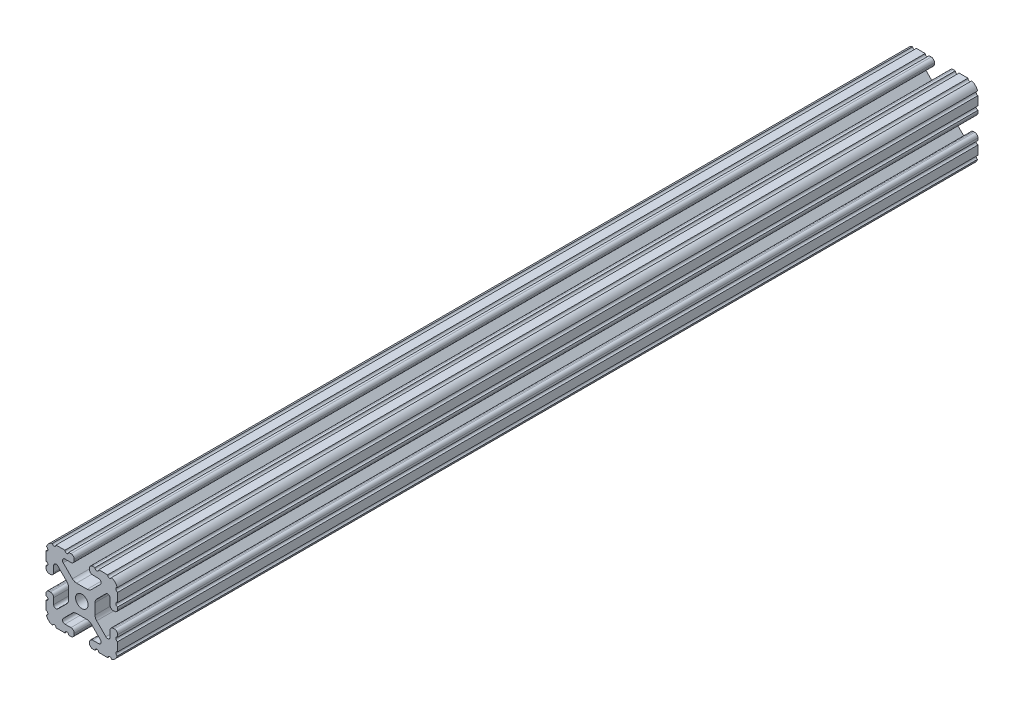
SolidWorks part; units mm, degrees
ref_plane "Front Plane" through (0, 0, 0) normal (0, 0, 1) x (1, 0, 0)
ref_plane "Top Plane" through (0, 0, 0) normal (0, 1, 0) x (1, 0, 0)
ref_plane "Right Plane" through (0, 0, 0) normal (1, 0, 0) x (0, 0, -1)
sketch "Sketch2" plane through (0, 0, 0) normal (0, 0, 1) x (1, 0, 0)
  line L0 (0, 19.05) -> (0, -19.05) construction
  line L1 (-19.05, 0) -> (19.05, 0) construction
  line L2 (4.064, -19.05) -> (19.05, -19.05)
  line L3 (19.05, -19.05) -> (19.05, -4.064)
  line L4 (4.064, -19.05) -> (4.064, -14.986)
  line L5 (4.064, -14.986) -> (12.1123, -14.986)
  line L6 (12.1123, -14.986) -> (4.1113, -6.985)
  line L7 (0, 0) -> (19.05, -19.05) construction
  line L8 (19.05, -4.064) -> (14.986, -4.064)
  line L9 (14.986, -4.064) -> (14.986, -12.1123)
  line L10 (14.986, -12.1123) -> (6.985, -4.1113)
  circle A0 centre (0, 0) radius 3.3274
  arc A1 (8.9963, -14.986) -> (9.909, -12.7826) centre (8.9963, -13.6953) ccw construction
  point P8 (0, -6.985)
  dimension "Center Hole Diameter" = 6.6548
  dimension "Rail Height" = 38.1
  dimension "Rail Width" = 38.1
  dimension "T-Slot Width" = 8.128
  dimension "Slot Inner Width" = 20.574
  dimension "Thickness" = 4.064
  dimension "Slot Depth" = 8.001
  dimension "D1" = 4.064
sketch "Sketch3" plane through (0, 0, 0) normal (1, 0, 0) x (0, 0, -1)
  line L0 (-228.6, -19.05) -> (228.6, -19.05) construction
  line L1 (-203.2, 0) -> (203.2, 0) construction
  dimension "Length" = 457.2
  dimension "D1" = 25.4
sketch "Sketch4" plane through (0, 0, 0) normal (0, 0, 1) x (1, 0, 0)
  line L0 (5.7912, -19.05) -> (14.3002, -19.05)
  line L1 (4.064, -19.05) -> (19.05, -19.05) construction
  line L2 (4.064, -19.05) -> (4.064, -14.986) construction
  line L3 (4.064, -14.986) -> (12.1123, -14.986) construction
  line L4 (4.064, -16.7132) -> (4.064, -17.3228)
  line L5 (5.7912, -14.986) -> (8.9963, -14.986)
  line L6 (0, -6.985) -> (2.833, -6.985)
  line L7 (12.1123, -14.986) -> (4.1113, -6.985) construction
  line L8 (5.0152, -7.8889) -> (9.909, -12.7826)
  line L9 (19.05, -19.05) -> (19.05, -4.064) construction
  line L10 (14.986, -12.1123) -> (6.985, -4.1113) construction
  line L11 (14.986, -4.064) -> (14.986, -12.1123) construction
  line L12 (14.986, -8.9963) -> (14.986, -5.7912)
  line L13 (19.05, -4.064) -> (14.986, -4.064) construction
  line L14 (16.7132, -4.064) -> (17.3228, -4.064)
  line L15 (19.05, -5.7912) -> (19.05, -14.3002)
  line L16 (12.7826, -9.909) -> (7.8889, -5.0152)
  line L17 (6.985, 0) -> (6.985, -2.833)
  line L18 (-19.05, 0) -> (19.05, 0) construction
  line L19 (0, -6.985) -> (0, -3.3274)
  line L20 (0, 19.05) -> (0, -19.05) construction
  line L21 (6.985, 0) -> (3.3274, 0)
  arc A0 (4.064, -17.3228) -> (5.7912, -19.05) centre (5.7912, -17.3228) ccw
  arc A2 (4.064, -16.7132) -> (5.7912, -14.986) centre (5.7912, -16.7132) cw
  arc A3 (8.9963, -14.986) -> (9.909, -12.7826) centre (8.9963, -13.6953) ccw
  arc A4 (2.833, -6.985) -> (5.0152, -7.8889) centre (2.833, -10.0711) cw
  arc A5 (14.3002, -19.05) -> (19.05, -14.3002) centre (14.3002, -14.3002) ccw
  arc A6 (12.7826, -9.909) -> (14.986, -8.9963) centre (13.6953, -8.9963) ccw
  arc A7 (14.986, -5.7912) -> (16.7132, -4.064) centre (16.7132, -5.7912) cw
  arc A8 (17.3228, -4.064) -> (19.05, -5.7912) centre (17.3228, -5.7912) cw
  arc A9 (7.8889, -5.0152) -> (6.985, -2.833) centre (10.0711, -2.833) cw
  circle A10 centre (0, 0) radius 3.3274 construction
  arc A11 (0, -3.3274) -> (3.3274, 0) centre (0, 0) ccw
  dimension "D1" = 4.7498
  dimension "D2" = 3.0861
  dimension "D3" = 1.7272
extrude "Boss-Extrude1" add sketch "Sketch4" along normal mid plane 457.2
sketch "Sketch5" plane through (0, 0, 0) normal (0, 0, 1) x (1, 0, 0)
  line L0 (4.064, -19.05) -> (19.05, -19.05) construction
  line L1 (5.7912, -14.986) -> (8.9963, -14.986) construction
  line L3 (0, 0) -> (19.05, -19.05) construction
  line L4 (8.9963, -14.986) -> (8.9963, -19.05) construction
  line L5 (12.1123, -14.986) -> (4.1113, -6.985) construction
  circle A0 centre (14.7395, -19.05) radius 1.016
  circle A1 centre (7.9803, -19.05) radius 1.016
  circle A2 centre (19.05, -14.7395) radius 1.016
  circle A3 centre (19.05, -7.9803) radius 1.016
  point P10 (7.3938, -14.986)
  point P12 (13.6953, -8.9963)
  dimension "D1" = 2.032
extrude "Cut-Extrude1" cut sketch "Sketch5" against normal through all both and the other way through all
mirror "Mirror1" about plane through (0, 0, 0) normal (1, 0, 0) of bodies 137 134
mirror "Mirror2" about plane through (0, 0, 0) normal (0, 1, 0) of bodies 135
equation "\"D1@Boss-Extrude1\"=\"Length@Sketch3\""
equation "\"D1@Sketch2\"=\"Thickness@Sketch2\""
equation "\"D2@Sketch4\"=\"Slot Inner Width@Sketch2\"*0.15"
equation "\"D1@Sketch4\"=\"D3@Sketch4\"*2.75"
equation "\"D3@Sketch4\"=\"Thickness@Sketch2\"*0.425"
equation "\"D1@Sketch5\"=\"Thickness@Sketch2\"*0.5"
